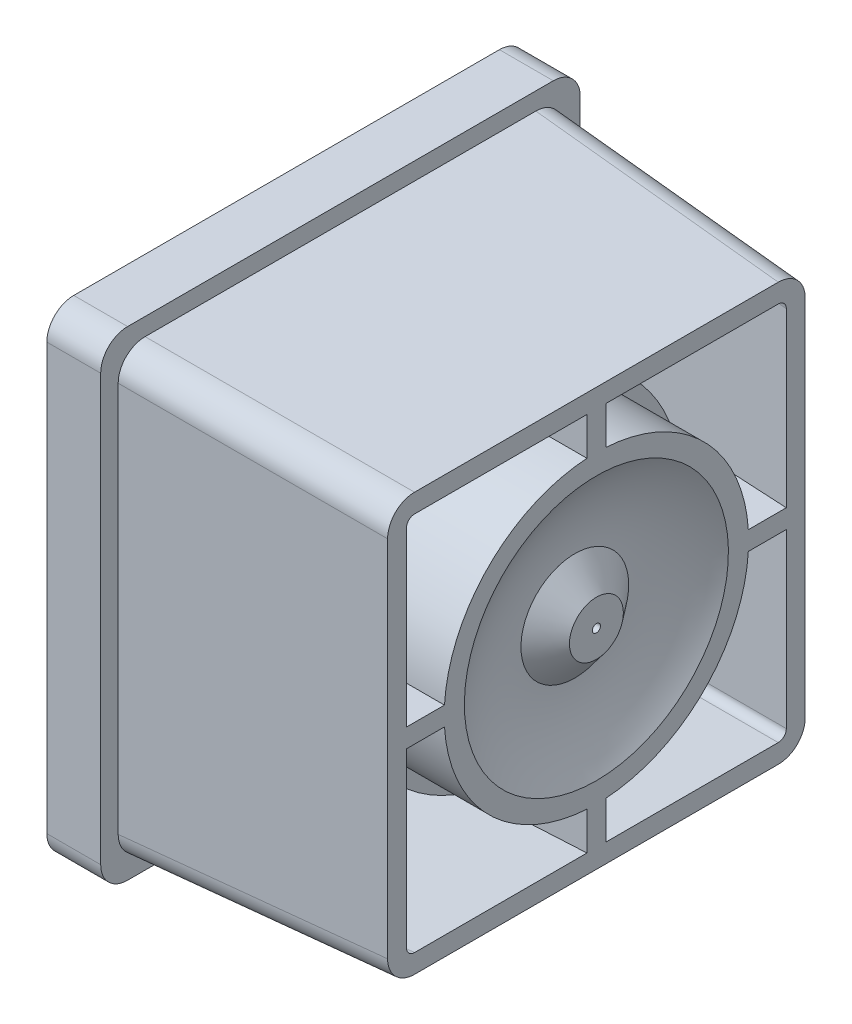
SolidWorks part; units mm, degrees
material "PET"
ref_plane "Front Plane" through (0, 0, 0) normal (0, 0, 1) x (1, 0, 0)
ref_plane "Top Plane" through (0, 0, 0) normal (0, 1, 0) x (1, 0, 0)
ref_plane "Right Plane" through (0, 0, 0) normal (1, 0, 0) x (0, 0, -1)
sketch "Sketch1" plane through (0, 0, 0) normal (1, 0, 0) x (0, 0, -1)
  line L1 (8.25, -8.25) -> (-8.25, -8.25)
  line L2 (8.25, -8.25) -> (8.25, 8.25)
  line L3 (8.25, 8.25) -> (-8.25, 8.25)
  line L4 (-8.25, -8.25) -> (-8.25, 8.25)
  line L5 (8.25, -8.25) -> (-8.25, 8.25) construction
  line L6 (8.25, 8.25) -> (-8.25, -8.25) construction
  point P0 (0, 0)
  dimension "D1" = 16.5
ref_plane "Plane1" through (9.5, 0, 0) normal (1, 0, 0) x (0, 0, -1)
sketch "Sketch2" plane through (9.5, 0, 0) normal (1, 0, 0) x (0, 0, -1)
  line L1 (7.75, -7.75) -> (-7.75, -7.75)
  line L2 (7.75, -7.75) -> (7.75, 7.75)
  line L3 (7.75, 7.75) -> (-7.75, 7.75)
  line L4 (-7.75, -7.75) -> (-7.75, 7.75)
  line L5 (7.75, -7.75) -> (-7.75, 7.75) construction
  line L6 (7.75, 7.75) -> (-7.75, -7.75) construction
  point P0 (0, 0)
  dimension "D1" = 15.5
loft "Loft1" add profiles "Sketch2", "Sketch1"
fillet "Fillet1" radius 1 4 edges
shell "Shell1" thickness 0.7
sketch "Sketch3" plane through (0, 0, 0) normal (1, 0, 0) x (0, 0, -1)
  line L1 (-8.9, -8.9) -> (8.9, -8.9)
  line L2 (-8.9, -8.9) -> (-8.9, 8.9)
  line L3 (-8.9, 8.9) -> (8.9, 8.9)
  line L4 (8.9, -8.9) -> (8.9, 8.9)
  line L5 (-8.9, -8.9) -> (8.9, 8.9) construction
  line L6 (-8.9, 8.9) -> (8.9, -8.9) construction
  point P0 (0, 0)
  dimension "D1" = 17.8
extrude "Boss-Extrude1" add sketch "Sketch3" against normal blind 2
fillet "Fillet2" radius 1 4 edges at (-1, 8.9, -8.9) (-1, -8.9, -8.9) (-1, -8.9, 8.9) (-1, 8.9, 8.9)
sketch "Sketch5" plane through (0, 0, 0) normal (0, 0, 1) x (1, 0, 0)
  line L0 (0, 7.549) -> (0, -7.549)
  line L1 (0, 7.549) -> (0, -7.549) construction
  line L2 (-2, 8.9) -> (-2, -8.9)
  line L3 (-2, 8.9) -> (-2, -8.9) construction
  line L4 (0, 0) -> (0, 6.15)
  line L5 (0, 6.15) -> (6.5, 6.15)
  line L6 (6.5, 6.15) -> (6.5, 5.65)
  line L7 (6.5, 5.65) -> (9.5, 5.65)
  line L8 (9.5, -6.7494) -> (9.5, 6.7494) construction
  line L9 (9.5, 5.65) -> (9.5, 4.9)
  line L10 (0, 0) -> (9.5, 0)
  line L11 (8.7, 2) -> (9.5, 1)
  line L12 (9.5, 1) -> (9.5, 0)
  line L13 (8.7, 2) -> (8.7, 1.7333) construction
  arc A0 (9.5, 4.9) -> (8.7, 2) centre (14.3563, 2) ccw
  dimension "D1" = 6.15
  dimension "D2" = 3
  dimension "D3" = 5.65
  dimension "D4" = 0.75
  dimension "D5" = 1
  dimension "D6" = 0.8
  dimension "D7" = 2
revolve "Revolve1" add sketch "Sketch5" angle 360 about L10
sketch "Sketch10" plane through (0, 0, 0) normal (1, 0, 0) x (0, 0, -1)
  line L0 (-12.7173, 0.35) -> (11.5372, 0.35)
  line L1 (11.5372, -0.35) -> (-12.7173, -0.35)
  line L2 (0.35, 13.7918) -> (0.35, -15.7606)
  line L3 (0.35, -15.7606) -> (-0.35, -15.7606)
  line L4 (7.549, -7.2494) -> (7.549, 7.2494)
  line L5 (7.2494, 7.549) -> (-7.2494, 7.549)
  line L6 (-7.549, 7.2494) -> (-7.549, -7.2494)
  line L7 (-7.2494, -7.549) -> (7.2494, -7.549)
  line L8 (7.549, -7.2494) -> (7.549, 7.2494)
  line L9 (7.2494, 7.549) -> (-7.2494, 7.549)
  line L10 (-7.549, 7.2494) -> (-7.549, -7.2494)
  line L11 (-7.2494, -7.549) -> (7.2494, -7.549)
  line L12 (-0.35, -15.7606) -> (-0.35, 13.7918)
  line L13 (-0.35, 13.7918) -> (0.35, 13.7918)
  line L14 (-12.7173, 0.35) -> (-12.7173, -0.35)
  line L15 (11.5372, 0.35) -> (11.5372, -0.35)
  line L16 (0, 13.7918) -> (0, 0) construction
  line L17 (0, 0) -> (11.5372, 0) construction
  circle A0 centre (0, 0) radius 5.65 construction
  circle A1 centre (0, 0) radius 5.65
  ellipse E4 centre (7.2486, -7.2486) end of major axis (7.4613, -7.4613) minor radius 0.3 (7.2494, -7.549) -> (7.549, -7.2494) ccw
  ellipse E5 centre (7.2486, 7.2486) end of major axis (7.4613, 7.4613) minor radius 0.3 (7.549, 7.2494) -> (7.2494, 7.549) ccw
  ellipse E6 centre (-7.2486, 7.2486) end of major axis (-7.4613, 7.4613) minor radius 0.3 (-7.2494, 7.549) -> (-7.549, 7.2494) ccw
  ellipse E7 centre (-7.2486, -7.2486) end of major axis (-7.4613, -7.4613) minor radius 0.3 (-7.549, -7.2494) -> (-7.2494, -7.549) ccw
  ellipse E8 centre (7.2486, -7.2486) end of major axis (7.4613, -7.4613) minor radius 0.3 (7.2494, -7.549) -> (7.549, -7.2494) ccw
  ellipse E9 centre (7.2486, 7.2486) end of major axis (7.4613, 7.4613) minor radius 0.3 (7.549, 7.2494) -> (7.2494, 7.549) ccw
  ellipse E10 centre (-7.2486, 7.2486) end of major axis (-7.4613, 7.4613) minor radius 0.3 (-7.2494, 7.549) -> (-7.549, 7.2494) ccw
  ellipse E11 centre (-7.2486, -7.2486) end of major axis (-7.4613, -7.4613) minor radius 0.3 (-7.549, -7.2494) -> (-7.2494, -7.549) ccw
  circle M19 centre (0, 0) radius 6.15
  line M21 (7.549, -7.2494) -> (7.549, 7.2494)
  line M23 (7.2494, 7.549) -> (-7.2494, 7.549)
  line M25 (-7.549, 7.2494) -> (-7.549, -7.2494)
  dimension "D2" = 0.7
  dimension "D1" = 0
extrude "Boss-Extrude2" add sketch "Sketch10" along normal up to surface (9.5 mm away) contours L12 L2 M19 M23 | A1 L2 L12 M19 | L1 L0 M21 M19 | A1 L1 L0 M19 | L12 L11 L2 M19 | A1 L12 L2 M19 | L1 L0 M19 M25 | A1 L0 L1 M19 up to face at (9.5, 0, 0)
sketch "Sketch6" plane through (0, 0, 0) normal (0, 0, 1) x (1, 0, 0)
  line L0 (-2, 8.9) -> (-2, -8.9)
  line L1 (-2, 8.9) -> (-2, -8.9) construction
  line L2 (-2, 5.4) -> (-0.2, 5.4)
  line L3 (-0.2, 5.4) -> (0.0021, 5.75)
  line L4 (0.0021, 5.75) -> (0.5021, 5.75)
  line L5 (0.5021, 5.75) -> (2.1506, 5.15)
  line L6 (2.1506, 5.15) -> (7.8, 5.15)
  line L7 (7.8, 5.15) -> (7.8, 4.2)
  line L8 (-2, 0) -> (7.8, 0)
  line L9 (-2, 5.4) -> (-2, 0)
  line L10 (9.5, -4.9) -> (9.5, 4.9) construction
  line L11 (7.8, 4.2) -> (4.2, 4.2)
  line L12 (4.2, 4.2) -> (4.2, 3.2)
  line L13 (4.2, 3.2) -> (7.8, 3.2)
  line L14 (7.8, 3.2) -> (7.8, 0)
  dimension "D1" = 5.4
  dimension "D2" = 0.35
  dimension "D3" = 1.8
  dimension "D4" = 60
  dimension "D5" = 0.5
  dimension "D6" = 20
  dimension "D7" = 5.15
  dimension "D8" = 1.7
  dimension "D9" = 3.6
  dimension "D10" = 1
  dimension "D11" = 3.2
revolve "Cut-Revolve1" cut sketch "Sketch6" angle 360 about L8
fillet "Fillet3" radius 0.5 1 edges at (4.2, -3.2, 0)
sketch "Sketch7" plane through (7.8, 0, 0) normal (-1, 0, 0) x (0, 0, 1)
  line L0 (0, 0) -> (0, 2.5) construction
  line L1 (0, 0) -> (0, -2.5) construction
  line L2 (-0.75, 2.5) -> (0.75, 2.5)
  line L3 (0.75, 2.5) -> (0.75, 0)
  line L4 (-0.75, 2.5) -> (-0.75, 0)
  line L5 (-0.75, 0) -> (-0.75, -1.75)
  circle A0 centre (0, 0) radius 0.75
  circle A2 centre (0, -2) radius 0.5
  arc A3 (-0.75, -1.75) -> (0, -2.5) centre (0, -1.75) ccw
  arc A4 (0.4999, -1.9922) -> (-0.3333, -0.6719) centre (-0.9999, -2.0156) ccw
  dimension "D2" = 1.5
  dimension "D3" = 1
  dimension "D4" = 1.5
  dimension "D1" = 5
extrude "Cut-Extrude1" cut sketch "Sketch7" against normal blind 0.5 contours A0 L3 L2 L4 | A0 | A2 A4 A0 L5 A3 | A2
sketch "Sketch8" plane through (0, 0, 0) normal (0, 0, 1) x (1, 0, 0)
  line L0 (8.3, 2.5) -> (8.3, -0.75)
  line L1 (8.3, -0.8975) -> (8.3, -2.5)
  line L2 (9.5, 1) -> (9.5, -1)
  line L3 (8.3, 2.5) -> (8.3, -0.75) construction
  line L4 (9.5, 1) -> (9.5, -1) construction
  line L5 (9.5, 0) -> (8.3, 0)
  line L6 (8.3, 0) -> (7.4366, 0)
  line L7 (7.4366, 0) -> (7.4366, 0.75)
  line L8 (7.4366, 0.75) -> (8.3, 0.75)
  line L9 (8.3, 0.75) -> (8.6464, 0.15)
  line L10 (8.6464, 0.15) -> (9.5, 0.15)
  line L11 (9.5, 0.15) -> (9.5, 0)
  dimension "D1" = 0.75
  dimension "D2" = 30
  dimension "D3" = 0.15
revolve "Cut-Revolve2" cut sketch "Sketch8" angle 360 about L5
